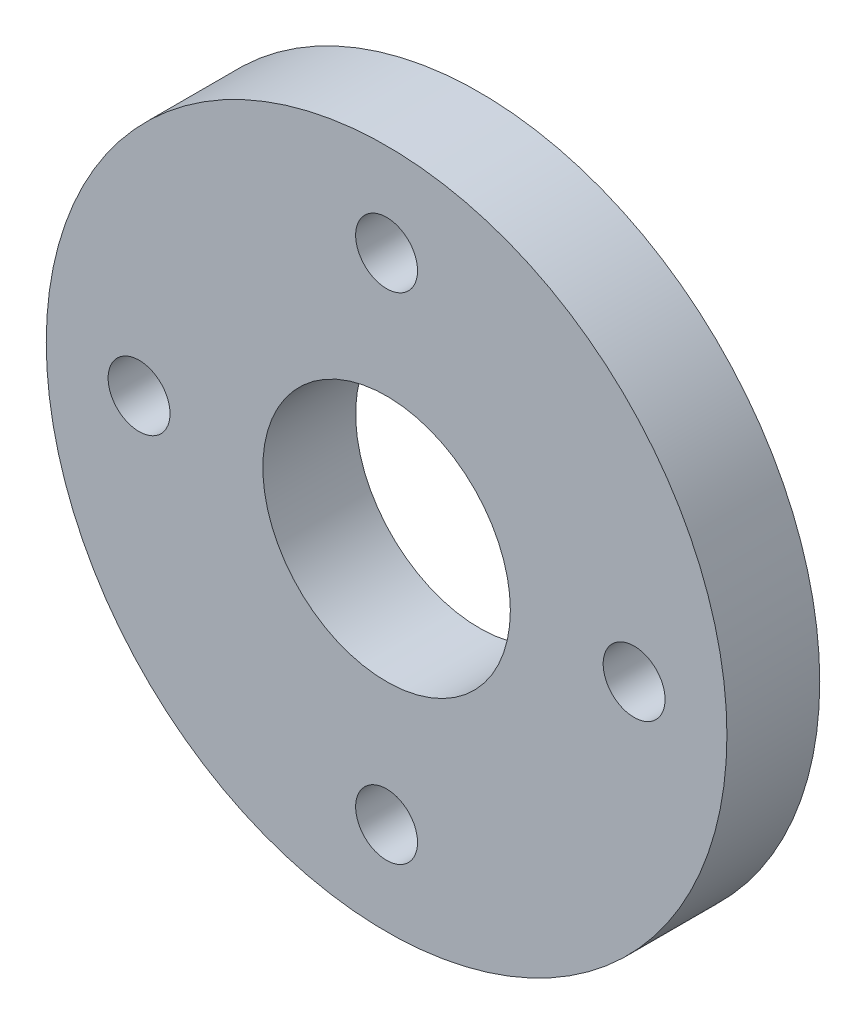
SolidWorks part; units mm, degrees
ref_plane "Plan de face" through (0, 0, 0) normal (0, 0, 1) x (1, 0, 0)
ref_plane "Plan de dessus" through (0, 0, 0) normal (0, 1, 0) x (1, 0, 0)
ref_plane "Plan de droite" through (0, 0, 0) normal (1, 0, 0) x (0, 0, -1)
sketch "Esquisse1" plane through (0, 0, 0) normal (0, 0, 1) x (1, 0, 0)
  circle A0 centre (0, 0) radius 11
extrude "Boss.-Extru.1" add sketch "Esquisse1" along normal blind 3
sketch "Esquisse2" plane through (0, 0, 3) normal (0, 0, 1) x (1, 0, 0)
  circle A0 centre (0, 0) radius 4
  circle A1 centre (0, 8) radius 1
  circle A2 centre (0, -8) radius 1
  circle A3 centre (8, 0) radius 1
  circle A4 centre (-8, 0) radius 1
  dimension "D1" = 8
  dimension "D2" = 8
  dimension "D3" = 8
  dimension "D4" = 8
extrude "Enlèv. mat.-Extru.1" cut sketch "Esquisse2" against normal blind 3
